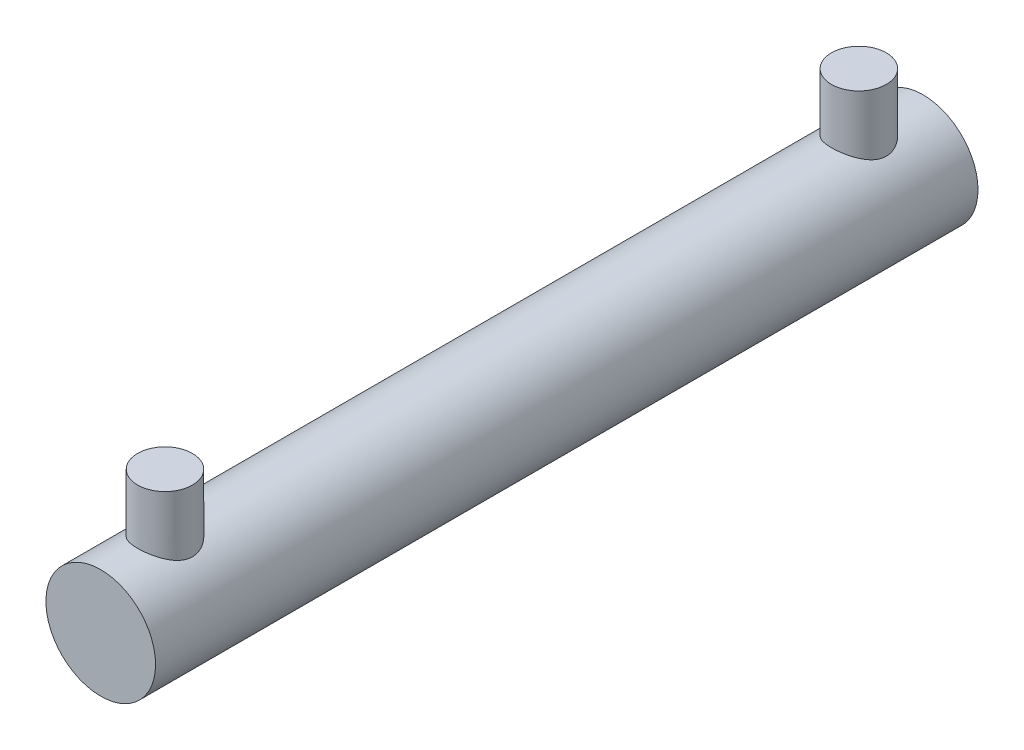
SolidWorks part; units mm, degrees
ref_plane "前视基准面" through (0, 0, 0) normal (0, 0, 1) x (1, 0, 0)
ref_plane "上视基准面" through (0, 0, 0) normal (0, 1, 0) x (1, 0, 0)
ref_plane "右视基准面" through (0, 0, 0) normal (1, 0, 0) x (0, 0, -1)
sketch "草图1" plane through (0, 0, 0) normal (0, 0, 1) x (1, 0, 0)
  circle A0 centre (0, 0) radius 20
  dimension "D1" = 40
extrude "凸台-拉伸1" add sketch "草图1" along normal mid plane 300
sketch "草图3" plane through (0, 0, 0) normal (0, 1, 0) x (1, 0, 0)
  line L0 (0, 0) -> (30.5667, 0) construction
  line L1 (30.5667, 0) -> (30.5667, 19.3409) construction
  circle A0 centre (0, 126.5515) radius 10
  circle A1 centre (0, -126.5515) radius 10
  point P8 (0, 126.5515)
  dimension "D1" = 20
extrude "凸台-拉伸2" add sketch "草图3" along normal blind 40
